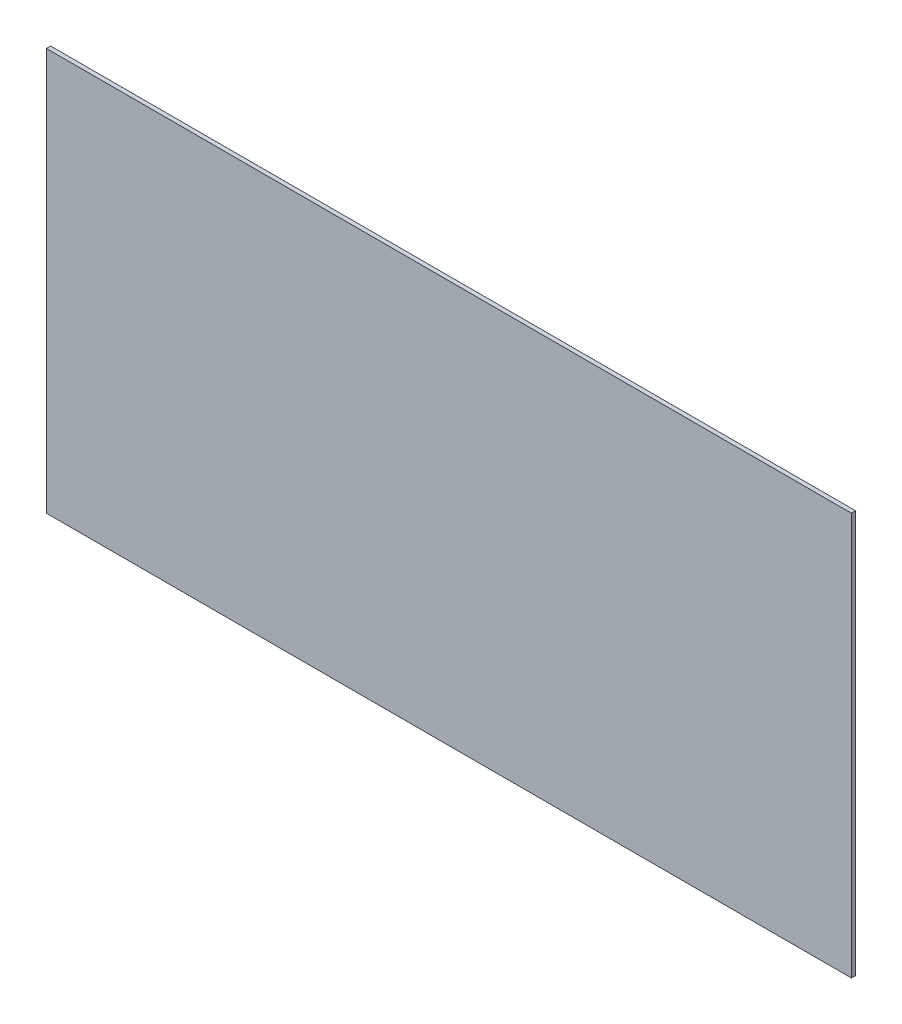
SolidWorks part; units mm, degrees
material "Beech"
ref_plane "Front Plane" through (0, 0, 0) normal (0, 0, 1) x (1, 0, 0)
ref_plane "Top Plane" through (0, 0, 0) normal (0, 1, 0) x (1, 0, 0)
ref_plane "Right Plane" through (0, 0, 0) normal (1, 0, 0) x (0, 0, -1)
sketch "Sketch1" plane through (0, 0, 0) normal (0, 0, 1) x (1, 0, 0)
  line L1 (0, 0) -> (1219.2, 0)
  line L2 (0, 0) -> (0, 609.6)
  line L3 (0, 609.6) -> (1219.2, 609.6)
  line L4 (1219.2, 0) -> (1219.2, 609.6)
  dimension "D1" = 1219.2
  dimension "D2" = 609.6
extrude "Boss-Extrude1" add sketch "Sketch1" along normal blind 6.35
ref_plane "Plane1" through (609.6, 0, 0) normal (1, 0, 0) x (0, 0, -1)
ref_plane "Plane2" through (0, 152.4, 0) normal (0, -1, 0) x (-1, 0, 0)
